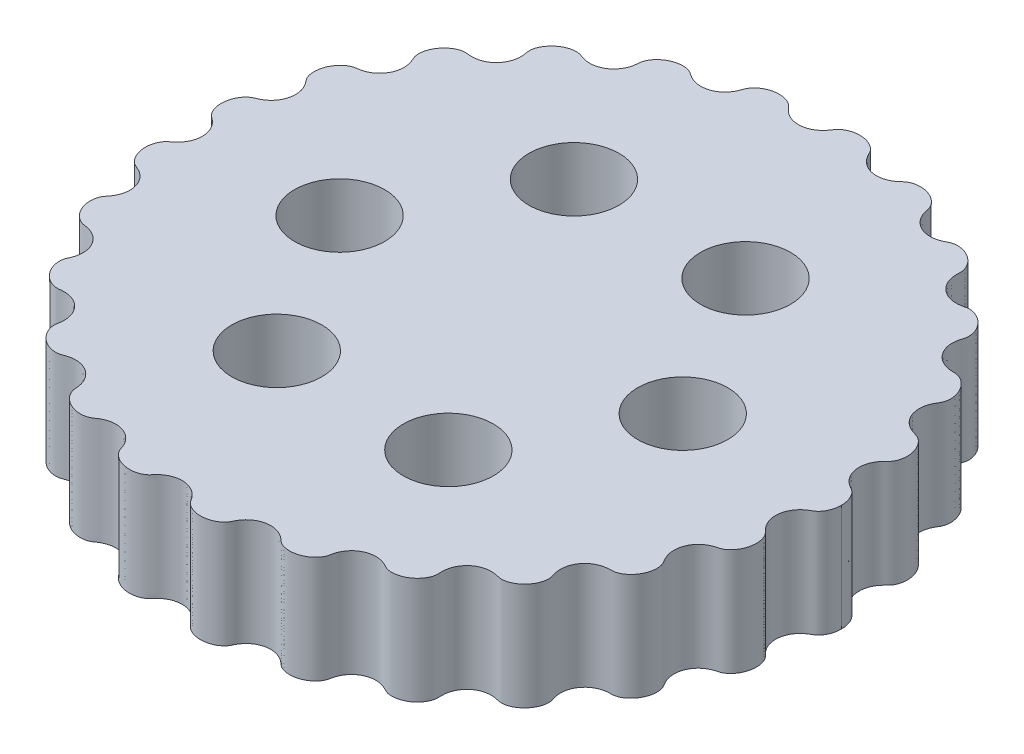
SolidWorks part; units mm, degrees
ref_plane "Front Plane" through (0, 0, 0) normal (0, 0, 1) x (1, 0, 0)
ref_plane "Top Plane" through (0, 0, 0) normal (0, 1, 0) x (1, 0, 0)
ref_plane "Right Plane" through (0, 0, 0) normal (1, 0, 0) x (0, 0, -1)
sketch "Sketch2" plane through (0, 0, 0) normal (0, 1, 0) x (1, 0, 0)
  line L0 (-15.4, 0) -> (14.4, 0) construction
  line L1 (0, 0) -> (0, -14.9128) construction
  line L2 (0, 0) -> (0, 14.9128) construction
  line L3 (-0.5, 0) -> (-0.5, -14.9128) construction
  line L4 (-0.5, 0) -> (-0.5, 14.9128) construction
  line L5 (14.4, 0) -> (15.5, 0) construction
  line L6 (0, 14.9128) -> (0, -14.9128) construction
  line L7 (5.9, 0) -> (9.1, 0) construction
  line L8 (5.9, 0) -> (7.5, 0)
  circle A0 centre (-0.5, 0) radius 16 construction
  circle A1 centre (15.5, 0) radius 1
  circle A2 centre (15.0351, -3.8291) radius 1
  circle A3 centre (13.6673, -7.4356) radius 1
  circle A4 centre (11.4762, -10.61) radius 1
  circle A5 centre (8.589, -13.1677) radius 1
  circle A6 centre (5.1737, -14.9603) radius 1
  circle A7 centre (1.4286, -15.8833) radius 1
  circle A8 centre (-2.4286, -15.8833) radius 1
  circle A9 centre (-6.1737, -14.9603) radius 1
  circle A10 centre (-9.589, -13.1677) radius 1
  circle A11 centre (-12.4762, -10.61) radius 1
  circle A12 centre (-14.6673, -7.4356) radius 1
  circle A13 centre (-16.0351, -3.8291) radius 1
  circle A14 centre (-16.5, 0) radius 1
  circle A15 centre (-16.0351, 3.8291) radius 1
  circle A16 centre (-14.6673, 7.4356) radius 1
  circle A17 centre (-12.4762, 10.61) radius 1
  circle A18 centre (-9.589, 13.1677) radius 1
  circle A19 centre (-6.1737, 14.9603) radius 1
  circle A20 centre (-2.4286, 15.8833) radius 1
  circle A21 centre (1.4286, 15.8833) radius 1
  circle A22 centre (5.1737, 14.9603) radius 1
  circle A23 centre (8.589, 13.1677) radius 1
  circle A24 centre (11.4762, 10.61) radius 1
  circle A25 centre (13.6673, 7.4356) radius 1
  circle A26 centre (15.0351, 3.8291) radius 1
  circle A27 centre (0, 0) radius 8
  circle A28 centre (8, 0) radius 2.1
  circle A29 centre (4, 6.9282) radius 2.1
  circle A30 centre (-4, 6.9282) radius 2.1
  circle A31 centre (-8, 0) radius 2.1
  circle A32 centre (-4, -6.9282) radius 2.1
  circle A33 centre (4, -6.9282) radius 2.1
  circle A34 centre (-1, 0) radius 8 construction
  circle A35 centre (3, -6.9282) radius 2.1
  circle A36 centre (-5, -6.9282) radius 2.1
  circle A37 centre (-9, 0) radius 2.1
  circle A38 centre (-5, 6.9282) radius 2.1
  circle A39 centre (3, 6.9282) radius 2.1
  circle A40 centre (7, 0) radius 2.1
  circle A41 centre (7.5, 0) radius 1.5
  circle A42 centre (3.5, -6.9282) radius 1.5
  circle A43 centre (-4.5, -6.9282) radius 1.5
  circle A44 centre (-8.5, 0) radius 1.5
  circle A45 centre (-4.5, 6.9282) radius 1.5
  circle A46 centre (3.5, 6.9282) radius 1.5
  spline S0 degree 4 number of poles 369 (14.1521, 3.1658) -> (-14.9531, 3.4358) construction
  spline S1 degree 4 number of poles 315 (14.4, 0) -> (-15.4, 0)
  spline S2 degree 4 number of poles 315 (14.4, 0) -> (-15.4, 0)
  spline S3 degree 4 number of poles 315 (-15.4, 0) -> (14.4, 0)
  spline S4 degree 4 number of poles 315 (-15.4, 0) -> (14.4, 0)
  point P80 (0, 0)
  dimension "D2" = 26
  dimension "D3" = 16
  dimension "D4" = 4.2
  dimension "D6" = 6
  dimension "D1" = 0.5
  dimension "D5" = 6
sketch "Sketch3" plane through (0, 0, 0) normal (0, 1, 0) x (1, 0, 0)
  spline S0 degree 4 number of poles 315 (-15.4, 0) -> (14.4, 0)
  spline S1 degree 4 number of poles 315 (-15.4, 0) -> (14.4, 0)
extrude "Boss-Extrude1" add sketch "Sketch3" against normal blind 5
sketch "Sketch4" plane through (0, 0, 0) normal (0, 1, 0) x (1, 0, 0)
  circle A0 centre (3, -6.9282) radius 2.1
  circle A1 centre (-5, -6.9282) radius 2.1
  circle A2 centre (-9, 0) radius 2.1
  circle A3 centre (-5, 6.9282) radius 2.1
  circle A4 centre (3, 6.9282) radius 2.1
  circle A5 centre (7, 0) radius 2.1
extrude "Cut-Extrude1" cut sketch "Sketch4" against normal through all
